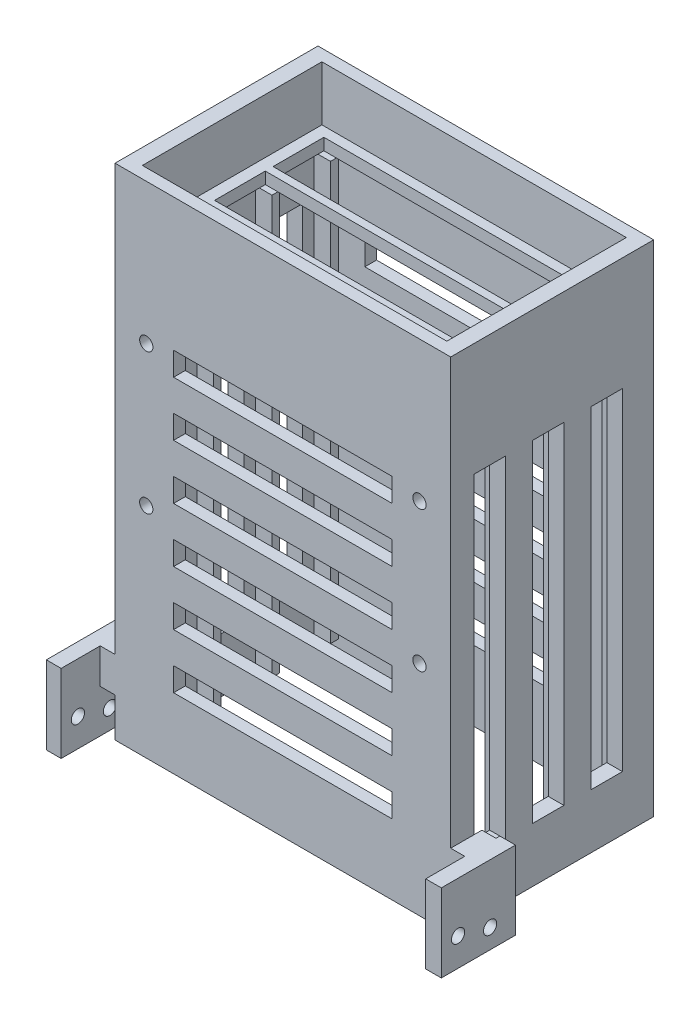
SolidWorks part; units mm, degrees
ref_plane "Спереди" through (0, 0, 0) normal (0, 0, 1) x (1, 0, 0)
ref_plane "Сверху" through (0, 0, 0) normal (0, 1, 0) x (1, 0, 0)
ref_plane "Справа" through (0, 0, 0) normal (1, 0, 0) x (0, 0, -1)
other "Configuration Table"
sketch "Эскиз1" plane through (0, 0, 0) normal (0, 0, 1) x (1, 0, 0)
  line L1 (-43, -64) -> (43, -64)
  line L2 (-43, -64) -> (-43, 64)
  line L3 (-43, 64) -> (43, 64)
  line L4 (43, -64) -> (43, 64)
extrude "Floor_1" add sketch "Эскиз1" along normal blind 3
ref_plane "Плоскость1" through (0, 0, 3) normal (0, 0, 1) x (1, 0, 0)
sketch "Эскиз2" plane through (0, 0, 3) normal (0, 0, 1) x (1, 0, 0)
  line L0 (43, 64) -> (-43, 64) construction
  line L1 (-43, -64) -> (-39, -64)
  line L2 (-43, -64) -> (-43, 64)
  line L3 (-43, 64) -> (-39, 64)
  line L4 (-39, -64) -> (-39, 64)
extrude "Left_wall_2" add sketch "Эскиз2" along normal blind 49
ref_plane "Плоскость2" through (0, 0, 3) normal (0, 0, 1) x (1, 0, 0)
sketch "Эскиз3" plane through (0, 0, 3) normal (0, 0, 1) x (1, 0, 0)
  line L0 (-39, -64) -> (43, -64) construction
  line L1 (39, -64) -> (43, -64)
  line L2 (39, -64) -> (39, 64)
  line L3 (39, 64) -> (43, 64)
  line L4 (43, -64) -> (43, 64)
extrude "Right_wall_3" add sketch "Эскиз3" along normal blind 49
ref_plane "Плоскость3" through (0, 0, 3) normal (0, 0, 1) x (1, 0, 0)
sketch "Эскиз4" plane through (0, 0, 3) normal (0, 0, 1) x (1, 0, 0)
  line L0 (-39, -64) -> (-39, 64) construction
  line L1 (-39, -62) -> (-34.8, -62)
  line L2 (-39, -62) -> (-39, 45)
  line L3 (-39, 45) -> (-34.8, 45)
  line L4 (-34.8, -62) -> (-34.8, 45)
extrude "Left_rail_0_4" add sketch "Эскиз4" along normal blind 2
ref_plane "Плоскость4" through (0, 0, 3) normal (0, 0, 1) x (1, 0, 0)
sketch "Эскиз5" plane through (0, 0, 3) normal (0, 0, 1) x (1, 0, 0)
  line L0 (39, 64) -> (39, -64) construction
  line L1 (34.8, -62) -> (39, -62)
  line L2 (34.8, -62) -> (34.8, 45)
  line L3 (34.8, 45) -> (39, 45)
  line L4 (39, -62) -> (39, 45)
extrude "Right_rail_0_5" add sketch "Эскиз5" along normal blind 2
ref_plane "Плоскость5" through (0, 0, 18) normal (0, 0, 1) x (1, 0, 0)
sketch "Эскиз6" plane through (0, 0, 18) normal (0, 0, 1) x (1, 0, 0)
  line L0 (-39, -64) -> (-39, 64) construction
  line L1 (-39, -62) -> (-34.8, -62)
  line L2 (-39, -62) -> (-39, 45)
  line L3 (-39, 45) -> (-34.8, 45)
  line L4 (-34.8, -62) -> (-34.8, 45)
extrude "Left_rail_1_6" add sketch "Эскиз6" along normal blind 2
ref_plane "Плоскость6" through (0, 0, 18) normal (0, 0, 1) x (1, 0, 0)
sketch "Эскиз7" plane through (0, 0, 18) normal (0, 0, 1) x (1, 0, 0)
  line L1 (34.8, -62) -> (39, -62)
  line L2 (34.8, -62) -> (34.8, 45)
  line L3 (34.8, 45) -> (39, 45)
  line L4 (39, -62) -> (39, 45)
extrude "Right_rail_1_7" add sketch "Эскиз7" along normal blind 2
ref_plane "Плоскость7" through (0, 0, 33) normal (0, 0, 1) x (1, 0, 0)
sketch "Эскиз8" plane through (0, 0, 33) normal (0, 0, 1) x (1, 0, 0)
  line L0 (-39, -64) -> (-39, 64) construction
  line L1 (-39, -62) -> (-34.8, -62)
  line L2 (-39, -62) -> (-39, 45)
  line L3 (-39, 45) -> (-34.8, 45)
  line L4 (-34.8, -62) -> (-34.8, 45)
extrude "Left_rail_2_8" add sketch "Эскиз8" along normal blind 2
ref_plane "Плоскость8" through (0, 0, 33) normal (0, 0, 1) x (1, 0, 0)
sketch "Эскиз9" plane through (0, 0, 33) normal (0, 0, 1) x (1, 0, 0)
  line L1 (34.8, -62) -> (39, -62)
  line L2 (34.8, -62) -> (34.8, 45)
  line L3 (34.8, 45) -> (39, 45)
  line L4 (39, -62) -> (39, 45)
extrude "Right_rail_2_9" add sketch "Эскиз9" along normal blind 2
ref_plane "Плоскость9" through (0, 0, 3) normal (0, 0, 1) x (1, 0, 0)
sketch "Эскиз10" plane through (0, 0, 3) normal (0, 0, 1) x (1, 0, 0)
  line L0 (-39, -64) -> (-39, 64) construction
  line L1 (-39, 47) -> (39, 47)
  line L2 (-39, 47) -> (-39, 50)
  line L3 (-39, 50) -> (39, 50)
  line L4 (39, 47) -> (39, 50)
extrude "Rear_stop_10" add sketch "Эскиз10" along normal blind 46
ref_plane "Плоскость10" through (0, 0, 49) normal (0, 0, 1) x (1, 0, 0)
sketch "Эскиз11" plane through (0, 0, 49) normal (0, 0, 1) x (1, 0, 0)
  line L1 (-43, -64) -> (43, -64)
  line L2 (-43, -64) -> (-43, 64)
  line L3 (-43, 64) -> (43, 64)
  line L4 (43, -64) -> (43, 64)
extrude "Roof_11" add sketch "Эскиз11" along normal blind 3
ref_plane "Плоскость11" through (-44, 0, 0) normal (1, 0, 0) x (0, 0, -1)
sketch "Эскиз12" plane through (-44, 0, 0) normal (1, 0, 0) x (0, 0, -1)
  line L1 (-8, -50) -> (-16, -50)
  line L2 (-8, -50) -> (-8, 35)
  line L3 (-8, 35) -> (-16, 35)
  line L4 (-16, -50) -> (-16, 35)
extrude "Side_airflow_0_12" cut sketch "Эскиз12" along normal blind 88
ref_plane "Плоскость12" through (-44, 0, 0) normal (1, 0, 0) x (0, 0, -1)
sketch "Эскиз13" plane through (-44, 0, 0) normal (1, 0, 0) x (0, 0, -1)
  line L1 (-23, -50) -> (-31, -50)
  line L2 (-23, -50) -> (-23, 35)
  line L3 (-23, 35) -> (-31, 35)
  line L4 (-31, -50) -> (-31, 35)
extrude "Side_airflow_1_13" cut sketch "Эскиз13" along normal blind 88
ref_plane "Плоскость13" through (-44, 0, 0) normal (1, 0, 0) x (0, 0, -1)
sketch "Эскиз14" plane through (-44, 0, 0) normal (1, 0, 0) x (0, 0, -1)
  line L1 (-38, -50) -> (-46, -50)
  line L2 (-38, -50) -> (-38, 35)
  line L3 (-38, 35) -> (-46, 35)
  line L4 (-46, -50) -> (-46, 35)
extrude "Side_airflow_2_14" cut sketch "Эскиз14" along normal blind 88
ref_plane "Плоскость14" through (0, 0, -1) normal (0, 0, 1) x (1, 0, 0)
sketch "Эскиз15" plane through (0, 0, -1) normal (0, 0, 1) x (1, 0, 0)
  line L1 (-28, -46) -> (28, -46)
  line L2 (-28, -46) -> (-28, -40)
  line L3 (-28, -40) -> (28, -40)
  line L4 (28, -46) -> (28, -40)
  line L5 (-28, -32) -> (28, -32)
  line L6 (-28, -32) -> (-28, -26)
  line L7 (-28, -26) -> (28, -26)
  line L8 (28, -32) -> (28, -26)
  line L9 (-28, -18) -> (28, -18)
  line L10 (-28, -18) -> (-28, -12)
  line L11 (-28, -12) -> (28, -12)
  line L12 (28, -18) -> (28, -12)
  line L13 (-28, -4) -> (28, -4)
  line L14 (-28, -4) -> (-28, 2)
  line L15 (-28, 2) -> (28, 2)
  line L16 (28, -4) -> (28, 2)
  line L17 (-28, 10) -> (28, 10)
  line L18 (-28, 10) -> (-28, 16)
  line L19 (-28, 16) -> (28, 16)
  line L20 (28, 10) -> (28, 16)
  line L21 (-28, 24) -> (28, 24)
  line L22 (-28, 24) -> (-28, 30)
  line L23 (-28, 30) -> (28, 30)
  line L24 (28, 24) -> (28, 30)
extrude "Floor_roof_airflow_15" cut sketch "Эскиз15" along normal blind 55
ref_plane "Плоскость15" through (0, 0, 48) normal (0, 0, 1) x (1, 0, 0)
sketch "Эскиз16" plane through (0, 0, 48) normal (0, 0, 1) x (1, 0, 0)
  circle A0 centre (-35, -8) radius 1.7
  circle A1 centre (35, -8) radius 1.7
  circle A2 centre (-35, 28) radius 1.7
  circle A3 centre (35, 28) radius 1.7
extrude "Base_roof_M3_16" cut sketch "Эскиз16" along normal blind 5
ref_plane "Плоскость16" through (0, -65, 0) normal (0, 1, 0) x (1, 0, 0)
sketch "Эскиз17" plane through (0, -65, 0) normal (0, 1, 0) x (1, 0, 0)
  circle A0 centre (-41, -46) radius 1.3
  circle A1 centre (41, -46) radius 1.3
ref_plane "Плоскость17" through (0, -65, 0) normal (0, 1, 0) x (1, 0, 0)
sketch "Эскиз18" plane through (0, -65, 0) normal (0, 1, 0) x (1, 0, 0)
  circle A0 centre (-41, -10) radius 1.3
  circle A1 centre (41, -10) radius 1.3
extrude "Tray_lock_M3_0_18" cut sketch "Эскиз18" along normal blind 12
ref_plane "Плоскость18" through (0, -65, 0) normal (0, 1, 0) x (1, 0, 0)
sketch "Эскиз19" plane through (0, -65, 0) normal (0, 1, 0) x (1, 0, 0)
  circle A0 centre (-41, -25) radius 1.3
  circle A1 centre (41, -25) radius 1.3
extrude "Tray_lock_M3_1_19" cut sketch "Эскиз19" along normal blind 12
ref_plane "Плоскость19" through (0, -65, 0) normal (0, 1, 0) x (1, 0, 0)
sketch "Эскиз20" plane through (0, -65, 0) normal (0, 1, 0) x (1, 0, 0)
  circle A0 centre (-41, -40) radius 1.3
  circle A1 centre (41, -40) radius 1.3
extrude "Tray_lock_M3_2_20" cut sketch "Эскиз20" along normal blind 12
ref_plane "Плоскость20" through (0, -65, 0) normal (0, 1, 0) x (1, 0, 0)
sketch "Эскиз21" plane through (0, -65, 0) normal (0, 1, 0) x (1, 0, 0)
  circle A0 centre (-41, -49.5) radius 1.3
  circle A1 centre (41, -49.5) radius 1.3
extrude "Panel_M3_pilots_1" cut sketch "Эскиз21" along normal blind 14
ref_plane "Плоскость21" through (0, 46, 0) normal (0, 1, 0) x (1, 0, 0)
sketch "Эскиз22" plane through (0, 46, 0) normal (0, 1, 0) x (1, 0, 0)
  line L1 (-36, -5.5) -> (36, -5.5)
  line L2 (-36, -5.5) -> (-36, -18.5)
  line L3 (-36, -18.5) -> (36, -18.5)
  line L4 (36, -5.5) -> (36, -18.5)
extrude "Rear_SATA_USB_passage_0_101" cut sketch "Эскиз22" along normal blind 7
ref_plane "Плоскость22" through (0, 46, 0) normal (0, 1, 0) x (1, 0, 0)
sketch "Эскиз23" plane through (0, 46, 0) normal (0, 1, 0) x (1, 0, 0)
  line L1 (-36, -20.5) -> (36, -20.5)
  line L2 (-36, -20.5) -> (-36, -33.5)
  line L3 (-36, -33.5) -> (36, -33.5)
  line L4 (36, -20.5) -> (36, -33.5)
extrude "Rear_SATA_USB_passage_1_102" cut sketch "Эскиз23" along normal blind 7
ref_plane "Плоскость23" through (0, 46, 0) normal (0, 1, 0) x (1, 0, 0)
sketch "Эскиз24" plane through (0, 46, 0) normal (0, 1, 0) x (1, 0, 0)
  line L1 (-36, -35.5) -> (36, -35.5)
  line L2 (-36, -35.5) -> (-36, -48.5)
  line L3 (-36, -48.5) -> (36, -48.5)
  line L4 (36, -35.5) -> (36, -48.5)
extrude "Rear_SATA_USB_passage_2_103" cut sketch "Эскиз24" along normal blind 7
ref_plane "Плоскость24" through (0, 0, 44) normal (0, 0, 1) x (1, 0, 0)
sketch "Эскиз25" plane through (0, 0, 44) normal (0, 0, 1) x (1, 0, 0)
  line L0 (43, -64) -> (43, 64) construction
  line L1 (43, -54) -> (50.6, -54)
  line L2 (43, -54) -> (43, -45)
  line L3 (43, -45) -> (50.6, -45)
  line L4 (50.6, -54) -> (50.6, -45)
extrude "Right_hinge_foot_104" add sketch "Эскиз25" along normal blind 8
ref_plane "Плоскость25" through (0, 0, 44) normal (0, 0, 1) x (1, 0, 0)
sketch "Эскиз26" plane through (0, 0, 44) normal (0, 0, 1) x (1, 0, 0)
  line L0 (-43, 64) -> (-43, -64) construction
  line L1 (-50.6, -54) -> (-43, -54)
  line L2 (-50.6, -54) -> (-50.6, -45)
  line L3 (-50.6, -45) -> (-43, -45)
  line L4 (-43, -54) -> (-43, -45)
extrude "Left_hinge_foot_105" add sketch "Эскиз26" along normal blind 8
ref_plane "Плоскость26" through (0, 0, 43) normal (0, 0, 1) x (1, 0, 0)
sketch "Эскиз27" plane through (0, 0, 43) normal (0, 0, 1) x (1, 0, 0)
  line L1 (46.6, -65) -> (50.6, -65)
  line L2 (46.6, -65) -> (46.6, -45)
  line L3 (46.6, -45) -> (50.6, -45)
  line L4 (50.6, -65) -> (50.6, -45)
extrude "Right_angle_bracket_106" add sketch "Эскиз27" along normal blind 19
ref_plane "Плоскость27" through (0, 0, 43) normal (0, 0, 1) x (1, 0, 0)
sketch "Эскиз28" plane through (0, 0, 43) normal (0, 0, 1) x (1, 0, 0)
  line L0 (-43, -45) -> (-50.6, -45) construction
  line L1 (-50.6, -65) -> (-46.8, -65)
  line L2 (-50.6, -65) -> (-50.6, -45)
  line L3 (-50.6, -45) -> (-46.8, -45)
  line L4 (-46.8, -65) -> (-46.8, -45)
extrude "Left_angle_bracket_107" add sketch "Эскиз28" along normal blind 19
ref_plane "Плоскость28" through (-52, 0, 0) normal (1, 0, 0) x (0, 0, -1)
sketch "Эскиз29" plane through (-52, 0, 0) normal (1, 0, 0) x (0, 0, -1)
  circle A0 centre (-49.5, -60) radius 1.7
  circle A1 centre (-57.7104, -57.8) radius 1.7
extrude "M3_fixed_15deg_hinge_108" cut sketch "Эскиз29" along normal blind 104
